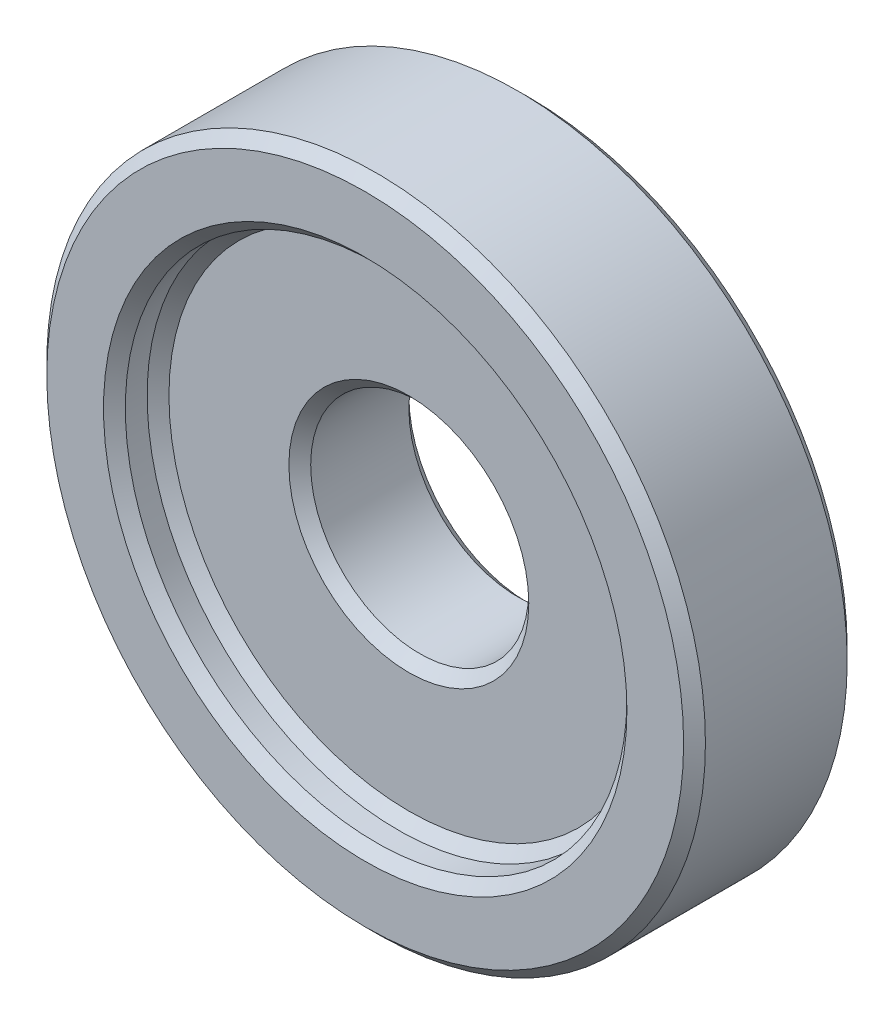
SolidWorks part; units mm, degrees
material "GR300"
ref_plane "Front Plane" through (0, 0, 0) normal (0, 0, 1) x (1, 0, 0)
ref_plane "Top Plane" through (0, 0, 0) normal (0, 1, 0) x (1, 0, 0)
ref_plane "Right Plane" through (0, 0, 0) normal (1, 0, 0) x (0, 0, -1)
sketch "Sketch2" plane through (0, 0, 0) normal (0, 0, 1) x (1, 0, 0)
  circle A0 centre (0, 0) radius 15.1
  circle A1 centre (0, 0) radius 5
  dimension "D1" = 30.2
  dimension "D2" = 10
extrude "Boss-Extrude1" add sketch "Sketch2" along normal blind 7.5
sketch "Sketch3" plane through (0, 0, 7.5) normal (0, 0, 1) x (1, 0, 0)
  circle A0 centre (0, 0) radius 11.5
  dimension "D1" = 23
extrude "Cut-Extrude1" cut sketch "Sketch3" against normal blind 2
chamfer "Chamfer1" distance 0.5 angle 45 6 edges at (11.5, 0, 5.5) (11.5, 0, 7.5) (5, 0, 0) (5, 0, 5.5) (15.1, 0, 0) (15.1, 0, 7.5)
